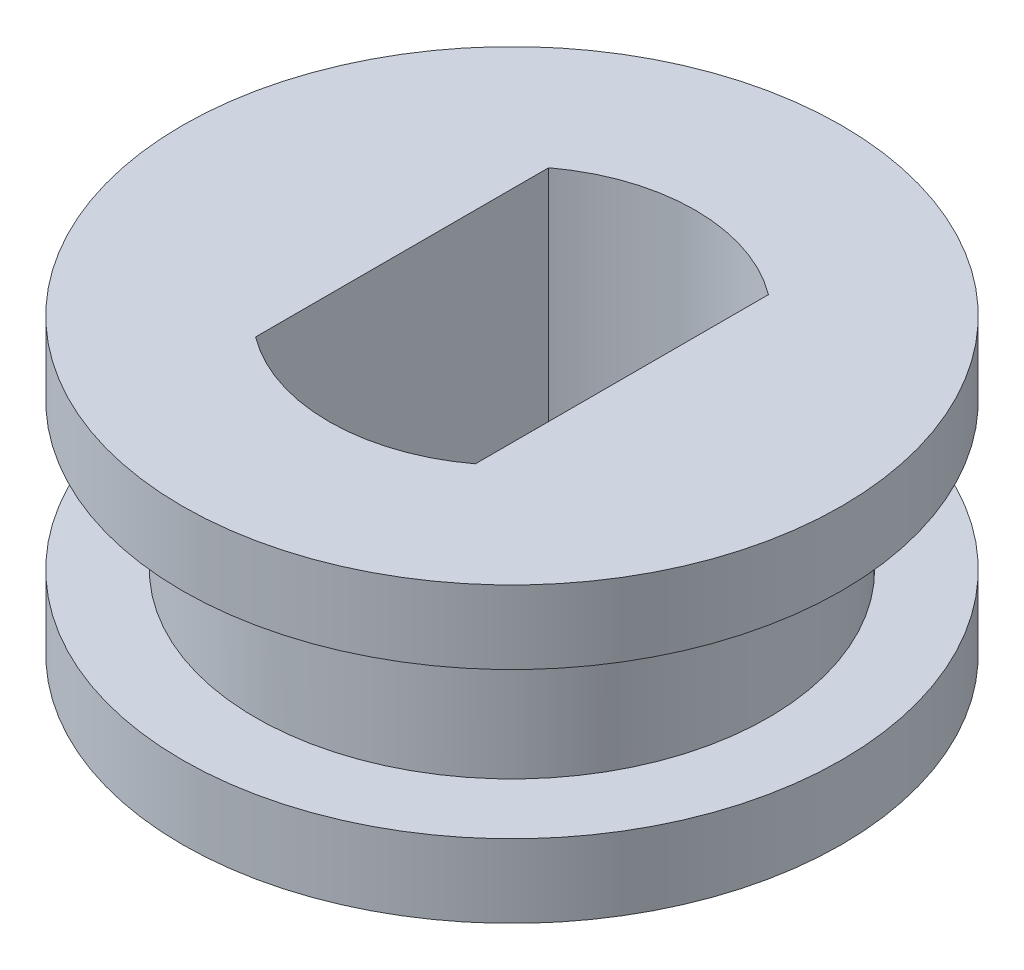
SolidWorks part; units mm, degrees
ref_plane "Front Plane" through (0, 0, 0) normal (0, 0, 1) x (1, 0, 0)
ref_plane "Top Plane" through (0, 0, 0) normal (0, 1, 0) x (1, 0, 0)
ref_plane "Right Plane" through (0, 0, 0) normal (1, 0, 0) x (0, 0, -1)
sketch "Sketch1" plane through (0, 0, 0) normal (0, 1, 0) x (1, 0, 0)
  line L2 (-1.5, 0) -> (1.5, 0) construction
  line L3 (-1.5, 2) -> (-1.5, -2)
  line L4 (1.5, 2) -> (1.5, -2)
  circle A0 centre (0, 0) radius 3.5
  arc A1 (-1.5, -2) -> (1.5, -2) centre (0, 0) ccw
  arc A2 (1.5, 2) -> (-1.5, 2) centre (0, 0) ccw
  dimension "D1" = 7
  dimension "D2" = 5
  dimension "D3" = 3
extrude "Boss-Extrude1" add sketch "Sketch1" along normal blind 4
sketch "Sketch2" plane through (0, 4, 0) normal (0, 1, 0) x (1, 0, 0)
  circle A0 centre (0, 0) radius 4.5
  circle A1 centre (0, 0) radius 3.5 construction
  circle A2 centre (0, 0) radius 3.5
  dimension "D1" = 1
extrude "Boss-Extrude2" add sketch "Sketch2" against normal blind 1
sketch "Sketch3" plane through (0, 0, 0) normal (0, -1, 0) x (1, 0, 0)
  circle A1 centre (0, 0) radius 4.5 construction
  circle A2 centre (0, 0) radius 4.5
  circle A4 centre (0, 0) radius 3.5 construction
  circle A5 centre (0, 0) radius 3.5
extrude "Boss-Extrude4" add sketch "Sketch3" against normal blind 1
